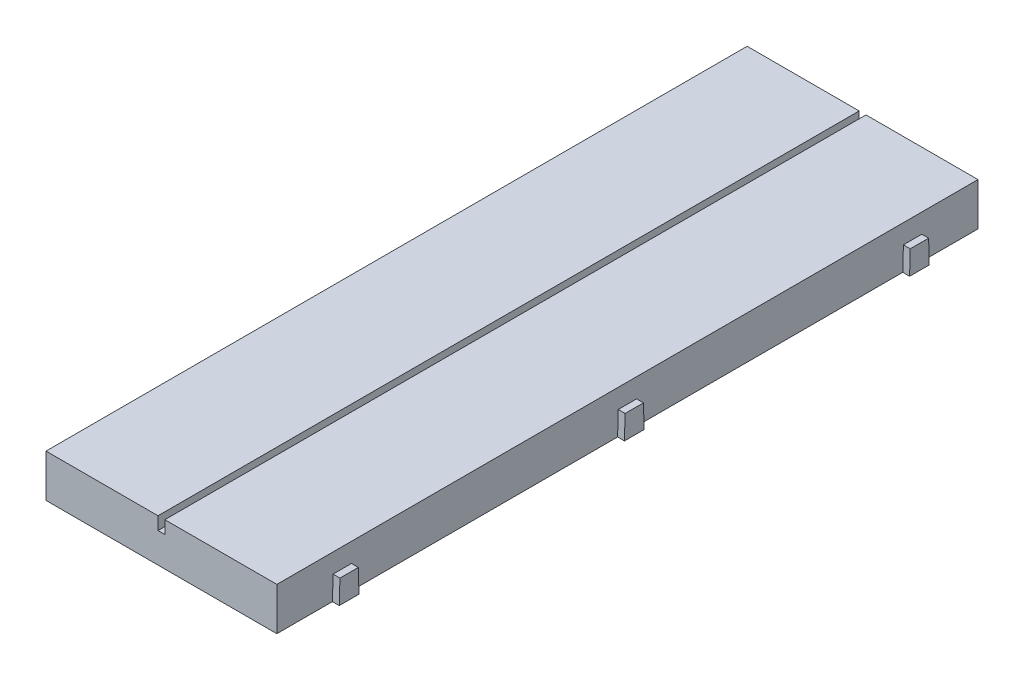
SolidWorks part; units mm, degrees
ref_plane "Front" through (0, 0, 0) normal (0, 0, 1) x (1, 0, 0)
ref_plane "Top" through (0, 0, 0) normal (0, 1, 0) x (1, 0, 0)
ref_plane "Right" through (0, 0, 0) normal (1, 0, 0) x (0, 0, -1)
sketch "Sketch1" plane through (0, 0, 0) normal (0, 0, 1) x (1, 0, 0)
  line L0 (-27, 10) -> (-27, 0)
  line L1 (-27, 10) -> (-0.8, 10)
  line L2 (-27, 0) -> (27, 0)
  line L3 (27, 10) -> (27, 0)
  line L4 (-27, 10) -> (27, 0) construction
  line L5 (-27, 0) -> (27, 10) construction
  line L6 (-0.8, 10) -> (0.8, 10) construction
  line L7 (-0.8, 10) -> (0.8, 10) construction
  line L8 (-0.8, 10) -> (-0.8, 7)
  line L9 (-0.8, 7) -> (0.8, 7)
  line L10 (0.8, 10) -> (0.8, 7)
  line L11 (0.8, 10) -> (27, 10)
  point P1 (0, 5)
  point P5 (0, 7)
  point P6 (0, 0)
  dimension "D1" = 54
  dimension "D2" = 10
  dimension "D3" = 3
  dimension "D4" = 1.6
extrude "Boss-Extrude1" add sketch "Sketch1" along normal blind 164
sketch "Sketch2" plane through (27, 0, 0) normal (1, 0, 0) x (0, 0, -1)
  line L0 (-151, 0) -> (-150.85, 5.5)
  line L1 (-164, 0) -> (0, 0) construction
  line L2 (-150.85, 5.5) -> (-146.55, 5.5)
  line L3 (-146.55, 5.5) -> (-146.4, 0)
  line L4 (-151, 0) -> (-146.4, 0)
  line L5 (-148.7, 0) -> (-148.7, 5.5) construction
  line L6 (-82, 10) -> (-82, 0) construction
  line L7 (-164, 10) -> (0, 10) construction
  line L8 (-13.15, 5.5) -> (-17.45, 5.5)
  line L9 (-17.45, 5.5) -> (-17.6, 0)
  line L10 (-13, 0) -> (-17.6, 0)
  line L11 (-13, 0) -> (-13.15, 5.5)
  line L12 (-84.3, 0) -> (-84.15, 5.5)
  line L13 (-84.15, 5.5) -> (-79.85, 5.5)
  line L14 (-79.85, 5.5) -> (-79.7, 0)
  line L15 (-79.7, 0) -> (-84.3, 0)
  point P19 (-82, 5.5)
  point P22 (-82, 0)
  dimension "D1" = 13
  dimension "D2" = 4.3
  dimension "D3" = 4.6
  dimension "D4" = 5.5
extrude "Boss-Extrude2" add sketch "Sketch2" along normal blind 1.6
mirror "Mirror1" about plane through (0, 0, 0) normal (1, 0, 0) of "Boss-Extrude2"
